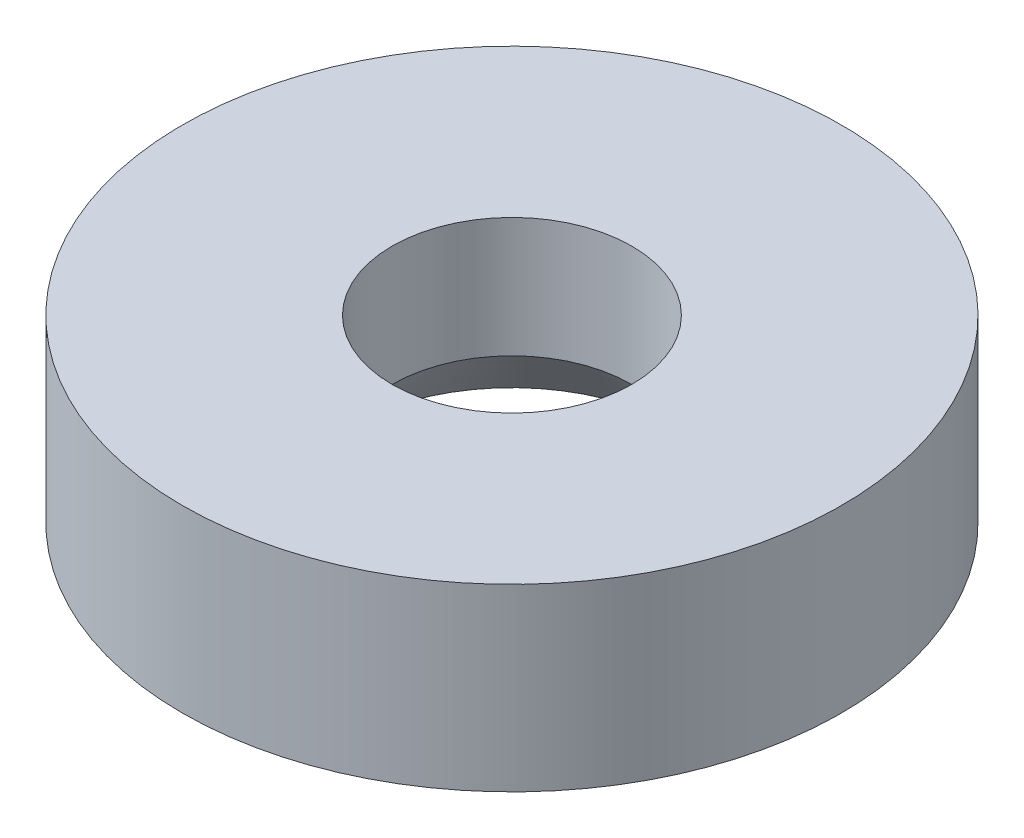
SolidWorks part; units mm, degrees
ref_plane "Front Plane" through (0, 0, 0) normal (0, 0, 1) x (1, 0, 0)
ref_plane "Top Plane" through (0, 0, 0) normal (0, 1, 0) x (1, 0, 0)
ref_plane "Right Plane" through (0, 0, 0) normal (1, 0, 0) x (0, 0, -1)
sketch "Sketch1" plane through (0, 0, 0) normal (0, 0, 1) x (1, 0, 0)
  line L0 (0, 1.2288) -> (0, -1.1847) construction
  line L1 (-1.5932, 0) -> (1.6407, 0) construction
  line L2 (0.4, 0.6) -> (1.1, 0.6)
  line L3 (1.1, 0.6) -> (1.1, 0)
  line L4 (1.1, 0) -> (0.5525, 0)
  line L5 (0.5525, 0) -> (0.4, 0.2)
  line L6 (0.4, 0.2) -> (0.4, 0.6)
  dimension "D1" = 0.4
  dimension "D2" = 1.1
  dimension "D3" = 0.6
  dimension "D4" = 0.2
revolve "Revolve1" add sketch "Sketch1" angle 360 about L0
